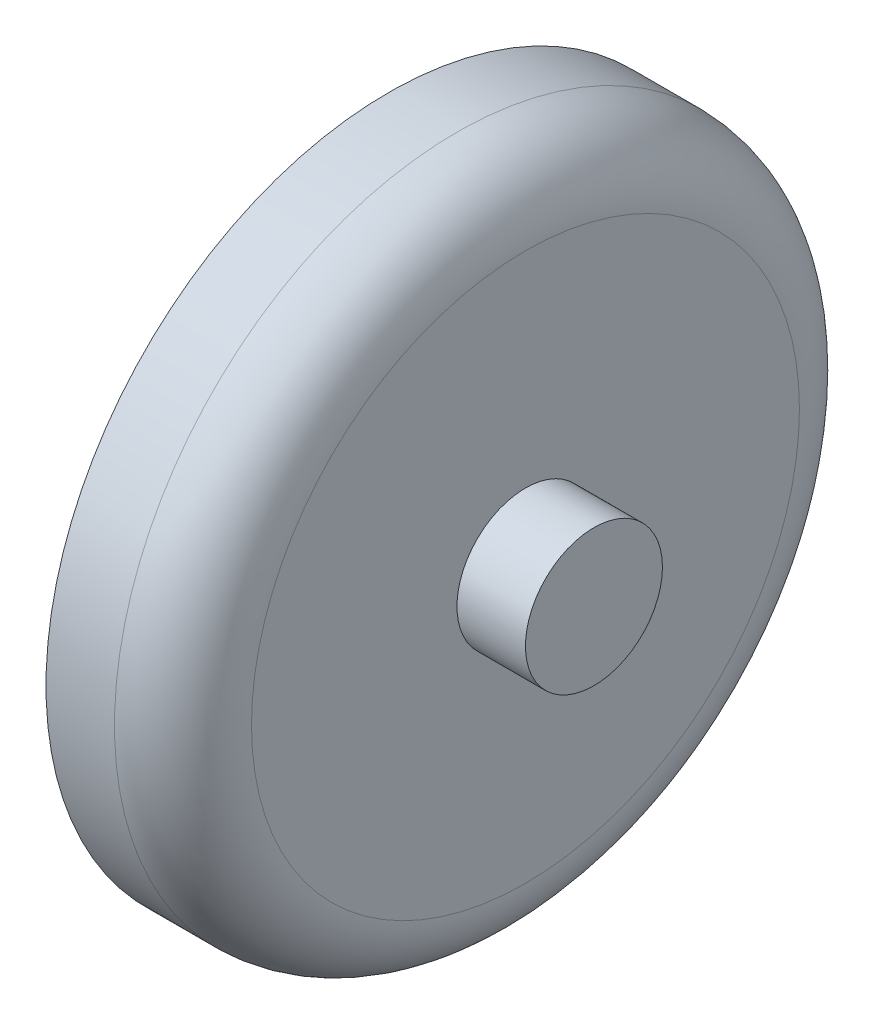
SolidWorks part; units mm, degrees
ref_plane "Front Plane" through (0, 0, 0) normal (0, 0, 1) x (1, 0, 0)
ref_plane "Top Plane" through (0, 0, 0) normal (0, 1, 0) x (1, 0, 0)
ref_plane "Right Plane" through (0, 0, 0) normal (1, 0, 0) x (0, 0, -1)
sketch "Sketch1" plane through (0, 0, 0) normal (1, 0, 0) x (0, 0, -1)
  circle A0 centre (0, 0) radius 25
  dimension "D1" = 50
extrude "Boss-Extrude1" add sketch "Sketch1" along normal blind 10
fillet "Fillet1" radius 5 1 edges at (10, 0, -25)
sketch "Sketch2" plane through (10, 0, 0) normal (1, 0, 0) x (0, 0, -1)
  circle A0 centre (0, 0) radius 5
  dimension "D1" = 10
extrude "Boss-Extrude2" add sketch "Sketch2" along normal blind 5
